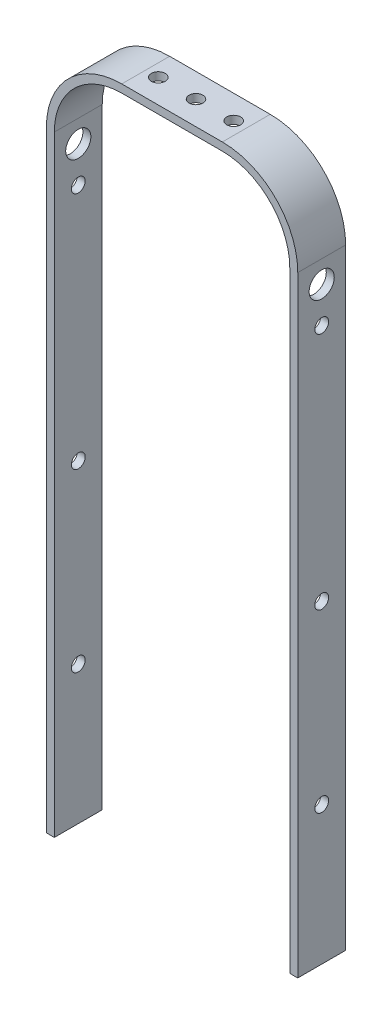
SolidWorks part; units mm, degrees
ref_plane "Front Plane" through (0, 0, 0) normal (0, 0, 1) x (1, 0, 0)
ref_plane "Top Plane" through (0, 0, 0) normal (0, 1, 0) x (1, 0, 0)
ref_plane "Right Plane" through (0, 0, 0) normal (1, 0, 0) x (0, 0, -1)
sketch "Sketch1" plane through (0, 0, 0) normal (0, 0, 1) x (1, 0, 0)
  line L0 (50, 0) -> (50, 243)
  line L1 (0, 0) -> (0, 109.6692) construction
  line L2 (46.825, 243) -> (46.825, 0)
  line L3 (46.825, 0) -> (50, 0)
  line L4 (20, 273) -> (-20, 273)
  line L6 (-20, 269.825) -> (20, 269.825)
  line L7 (-46.825, 0) -> (-50, 0)
  line L8 (-46.825, 243) -> (-46.825, 0)
  line L9 (-50, 0) -> (-50, 243)
  arc A0 (50, 243) -> (20, 273) centre (20, 243) ccw
  arc A1 (20, 269.825) -> (46.825, 243) centre (20, 243) cw
  arc A2 (-20, 269.825) -> (-46.825, 243) centre (-20, 243) ccw
  arc A3 (-50, 243) -> (-20, 273) centre (-20, 243) cw
  dimension "D4" = 26.825
  dimension "D5" = 273
  dimension "D1" = 100
  dimension "D2" = 46.825
extrude "Boss-Extrude1" add sketch "Sketch1" along normal mid plane 19.05
sketch "Sketch12" plane through (0, 273, 0) normal (0, 1, 0) x (1, 0, 0)
  line L0 (-20, -9.525) -> (-20, 9.525) construction
  line L1 (20, -9.525) -> (20, 9.525) construction
  circle A0 centre (0, 0) radius 2.75
  circle A1 centre (-15, 0) radius 2.75
  circle A4 centre (15, 0) radius 2.75
  dimension "D1" = 5.5
  dimension "D2" = 5
  dimension "D3" = 5
extrude "Cut-Extrude2" cut sketch "Sketch12" against normal through all
sketch "Sketch13" plane through (50, 0, 0) normal (1, 0, 0) x (0, 0, -1)
  line L0 (0, 243) -> (0, 0) construction
  line L1 (-9.525, 243) -> (9.525, 243) construction
  circle A0 centre (0, 220) radius 2.75
  circle A1 centre (0, 125) radius 2.75
  circle A2 centre (0, 55) radius 2.75
  dimension "D1" = 5.5
  dimension "D2" = 23
  dimension "D3" = 95
  dimension "D4" = 70
extrude "Cut-Extrude3" cut sketch "Sketch13" against normal through all both and the other way through all
sketch "Sketch14" plane through (50, 0, 0) normal (1, 0, 0) x (0, 0, -1)
  line L0 (-9.525, 243) -> (9.525, 243) construction
  circle A0 centre (0, 234.175) radius 5
  dimension "D1" = 10
  dimension "D2" = 8.825
extrude "Cut-Extrude4" cut sketch "Sketch14" against normal through all
